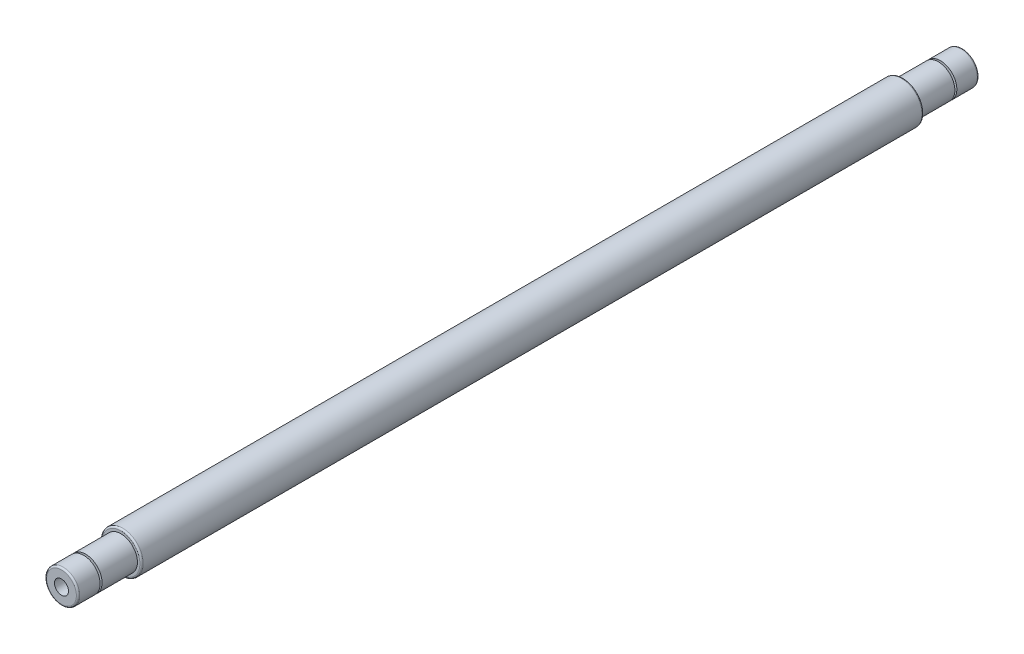
SolidWorks part; units mm, degrees
ref_plane "Ön Düzlem" through (0, 0, 0) normal (0, 0, 1) x (1, 0, 0)
ref_plane "Üst Düzlem" through (0, 0, 0) normal (0, 1, 0) x (1, 0, 0)
ref_plane "Sağ Düzlem" through (0, 0, 0) normal (1, 0, 0) x (0, 0, -1)
sketch "Çizim1" plane through (0, 0, 0) normal (0, 0, 1) x (1, 0, 0)
  circle A0 centre (0, 0) radius 12.5
  dimension "D1" = 25
extrude "Yükseklik-Ekstrüzyon1" add sketch "Çizim1" along normal blind 546
sketch "Çizim2" plane through (0, 0, 546) normal (0, 0, 1) x (1, 0, 0)
  circle A0 centre (0, 0) radius 4.25
  dimension "D1" = 8.5
extrude "Kes-Ekstrüzyon1" cut sketch "Çizim2" against normal blind 20
cosmetic thread "Kozmetik Diş Açma2" parameters "D2"=10
sketch "Çizim3" plane through (0, 0, 0) normal (0, 0, -1) x (-1, 0, 0)
  circle A0 centre (0, 0) radius 4.25
  dimension "D1" = 8.5
extrude "Kes-Ekstrüzyon2" cut sketch "Çizim3" against normal blind 20
cosmetic thread "Kozmetik Diş Açma1" parameters "D2"=10
sketch "Çizim4" plane through (0, 0, 546) normal (0, 0, 1) x (1, 0, 0)
  circle A0 centre (0, 0) radius 12.5
  circle A1 centre (0, 0) radius 10
  dimension "D1" = 20
  dimension "D2" = 25
extrude "Kes-Ekstrüzyon3" cut sketch "Çizim4" against normal blind 36
sketch "Çizim5" plane through (0, 0, 0) normal (0, 0, -1) x (-1, 0, 0)
  circle A0 centre (0, 0) radius 10
  circle A1 centre (0, 0) radius 12.5
  dimension "D1" = 25
  dimension "D2" = 20
extrude "Kes-Ekstrüzyon4" cut sketch "Çizim5" against normal blind 36
sketch "Çizim8" plane through (0, 0, 0) normal (0, 1, 0) x (1, 0, 0)
  line L0 (-10, 0) -> (-10, -36) construction
  line L1 (-11.85, -13.4) -> (-8.15, -13.4)
  line L2 (-11.85, -13.4) -> (-11.85, -14.6)
  line L3 (-11.85, -14.6) -> (-8.15, -14.6)
  line L4 (-8.15, -13.4) -> (-8.15, -14.6)
  line L5 (-11.85, -13.4) -> (-8.15, -14.6) construction
  line L6 (-11.85, -14.6) -> (-8.15, -13.4) construction
  line L8 (0, 0) -> (0, -21.8491) construction
  line L10 (-11.85, -531.4) -> (-8.15, -531.4)
  line L11 (-11.85, -531.4) -> (-11.85, -532.6)
  line L12 (-11.85, -532.6) -> (-8.15, -532.6)
  line L13 (-8.15, -531.4) -> (-8.15, -532.6)
  line L14 (-11.85, -531.4) -> (-8.15, -532.6) construction
  line L15 (-11.85, -532.6) -> (-8.15, -531.4) construction
  line L16 (-10, -510) -> (-10, -546) construction
  line L21 (-10, -546) -> (10, -546) construction
  line L22 (10, 0) -> (-10, 0) construction
  line L23 (4.25, 0) -> (-4.25, 0) construction
  point P0 (-10, -14)
  point P12 (-10, -532)
  dimension "D1" = 1.2
  dimension "D2" = 14.6
  dimension "D3" = 8.15
  dimension "D4" = 8.15
  dimension "D5" = 14.6
  dimension "D6" = 1.2
revolve "Kes-Döndür1" cut sketch "Çizim8" angle 360 about L8
fillet "Radyus1" radius 1 4 edges at (10, 0, 546) (12.5, 0, 510) (-12.5, 0, 36) (-10, 0, 0)
